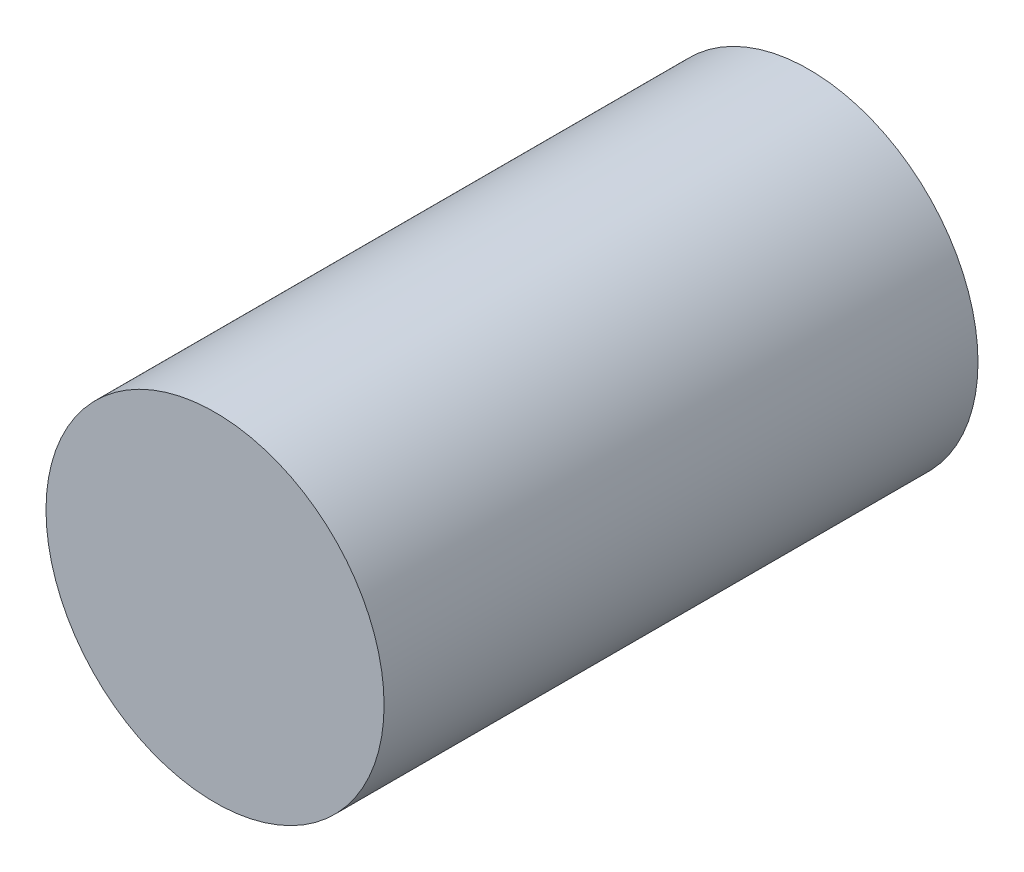
SolidWorks part; units mm, degrees
ref_plane "前基準面" through (0, 0, 0) normal (0, 0, 1) x (1, 0, 0)
ref_plane "上基準面" through (0, 0, 0) normal (0, 1, 0) x (1, 0, 0)
ref_plane "右基準面" through (0, 0, 0) normal (1, 0, 0) x (0, 0, -1)
sketch "草圖1" plane through (0, 0, 0) normal (0, 0, 1) x (1, 0, 0)
  circle A0 centre (0, 0) radius 18.5
  dimension "D1" = 37
extrude "伸長1" add sketch "草圖1" along normal blind 65
